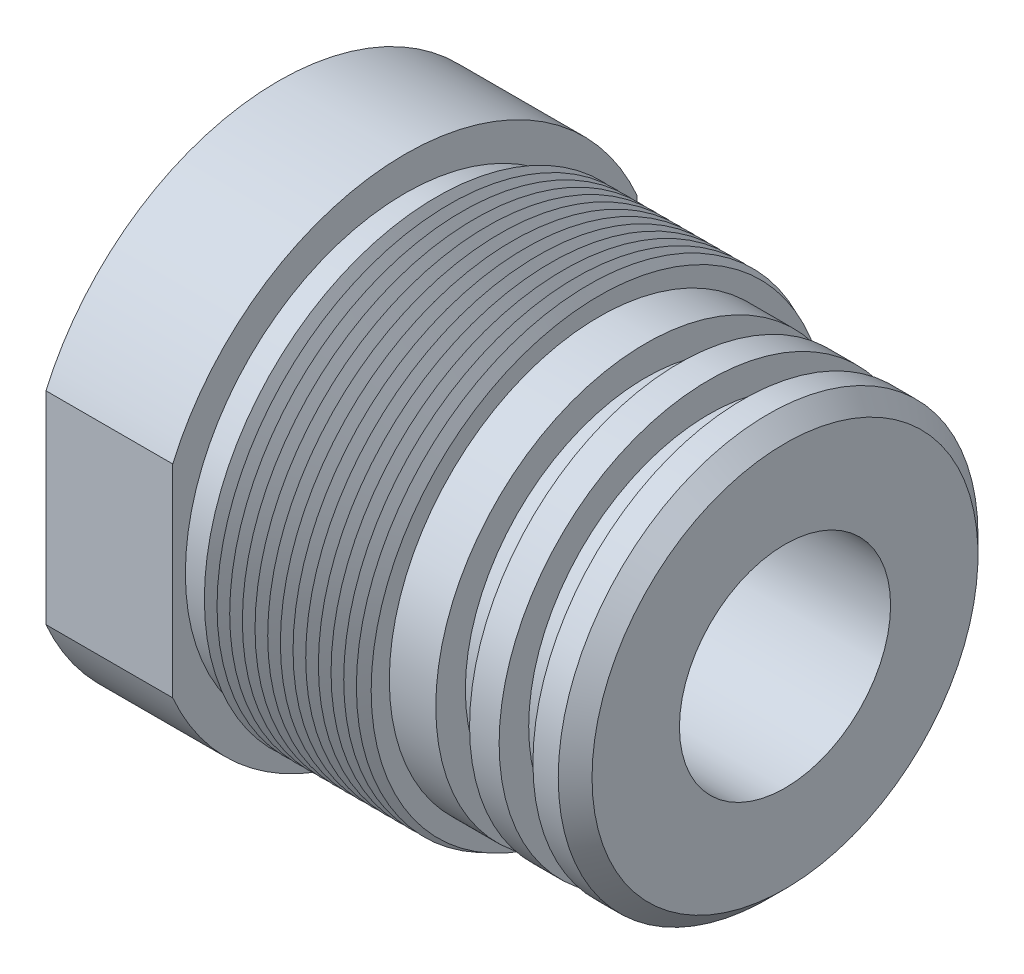
SolidWorks part; units mm, degrees
ref_plane "Front Plane" through (0, 0, 0) normal (0, 0, 1) x (1, 0, 0)
ref_plane "Top Plane" through (0, 0, 0) normal (0, 1, 0) x (1, 0, 0)
ref_plane "Right Plane" through (0, 0, 0) normal (1, 0, 0) x (0, 0, -1)
sketch "Sketch1" plane through (0, 0, 0) normal (0, 0, 1) x (1, 0, 0)
  line L0 (0, 0) -> (85.0332, 0) construction
  line L1 (0, 12.5) -> (60, 12.5)
  line L2 (0, 12.5) -> (0, 30)
  line L3 (0, 30) -> (15, 30)
  line L4 (15, 30) -> (15, 26)
  line L5 (15, 26) -> (18, 26)
  line L6 (18, 26) -> (18.75, 27.5)
  line L7 (18.75, 27.5) -> (19.5, 26)
  line L9 (19.5, 26) -> (20.25, 27.5)
  line L10 (20.25, 27.5) -> (21, 26)
  line L11 (21, 26) -> (21.75, 27.5)
  line L12 (21.75, 27.5) -> (22.5, 26)
  line L13 (22.5, 26) -> (23.25, 27.5)
  line L14 (23.25, 27.5) -> (24, 26)
  line L15 (24, 26) -> (24.75, 27.5)
  line L16 (24.75, 27.5) -> (25.5, 26)
  line L17 (25.5, 26) -> (26.25, 27.5)
  line L18 (26.25, 27.5) -> (27, 26)
  line L19 (27, 26) -> (27.75, 27.5)
  line L20 (27.75, 27.5) -> (28.5, 26)
  line L21 (28.5, 26) -> (29.25, 27.5)
  line L22 (29.25, 27.5) -> (30, 26)
  line L23 (30, 26) -> (30.75, 27.5)
  line L24 (30.75, 27.5) -> (31.5, 26)
  line L25 (31.5, 26) -> (32.25, 27.5)
  line L26 (32.25, 27.5) -> (33, 26)
  line L27 (33, 26) -> (33.75, 27.5)
  line L28 (33.75, 27.5) -> (34.5, 26)
  line L29 (34.5, 26) -> (35.25, 27.5)
  line L30 (35.25, 27.5) -> (36, 26)
  line L31 (36, 26) -> (36.75, 27.5)
  line L32 (36.75, 27.5) -> (37.5, 26)
  line L33 (37.5, 26) -> (38, 27)
  line L34 (58, 24.85) -> (60, 22.85)
  line L35 (60, 12.5) -> (60, 22.85)
  line L36 (58, 24.85) -> (55, 24.85)
  line L37 (38, 24.85) -> (38, 27)
  line L39 (38.25, 27.5) -> (39, 26) [skipped]
  line L40 (51, 24.85) -> (51, 21.35)
  line L41 (51, 21.35) -> (55, 21.35)
  line L42 (55, 24.85) -> (55, 21.35)
  line L44 (43.5, 24.85) -> (43.5, 21.35)
  line L45 (43.5, 21.35) -> (47.5, 21.35)
  line L46 (47.5, 24.85) -> (47.5, 21.35)
  line L47 (51, 24.85) -> (47.5, 24.85)
  line L48 (43.5, 24.85) -> (38, 24.85)
  dimension "D1" = 25
  dimension "D2" = 60
  dimension "D3" = 15
  dimension "D4" = 1.5
  dimension "D5" = 27.5
  dimension "D7" = 0.75
  dimension "D8" = 3
  dimension "D10" = 49.7
  dimension "D11" = 23
  dimension "D12" = 60
  dimension "D13" = 4
  dimension "D14" = 3.5
  dimension "D15" = 4
  dimension "D16" = 5
  dimension "D17" = 3.5
  dimension "D18" = 3.5
  dimension "D9" = 14
revolve "Revolve1" add sketch "Sketch1" angle 360 about L0
sketch "Sketch2" plane through (0, 0, 0) normal (-1, 0, 0) x (0, 0, 1)
  line L1 (-27.5, -38.3497) -> (27.5, -38.3497)
  line L2 (-27.5, -38.3497) -> (-27.5, 38.3497)
  line L3 (-27.5, 38.3497) -> (27.5, 38.3497)
  line L4 (27.5, -38.3497) -> (27.5, 38.3497)
  line L5 (-27.5, -38.3497) -> (27.5, 38.3497) construction
  line L6 (-27.5, 38.3497) -> (27.5, -38.3497) construction
  point P0 (0, 0)
  dimension "D1" = 55
extrude "Cut-Extrude1" cut sketch "Sketch2" against normal blind 17 flip side to cut
sketch "Sketch3" plane through (0, 0, 0) normal (0, 1, 0) x (1, 0, 0)
  line L0 (0, 12.5) -> (0.1287, 12.5) construction
  line L1 (60, 12.5) -> (0, 12.5) construction
  line L3 (0.1287, 15) -> (4.1287, 15) construction
  line L4 (4.1287, 15) -> (4.1287, 11.2199)
  line L5 (4.1287, 11.2199) -> (0.1287, 11.2199)
  line L6 (0.1287, 11.2199) -> (0.1287, 12.5)
  line L7 (0, 0) -> (26.0795, 0) construction
  line L8 (0.1287, 12.5) -> (61.3994, 12.5) construction
  line L9 (14.1287, 10.535) -> (22.1287, 10.535)
  line L10 (14.1287, 10.535) -> (14.1287, 18)
  line L11 (14.1287, 18) -> (22.1287, 18)
  line L12 (22.1287, 10.535) -> (22.1287, 18)
  line L13 (32.1287, 12.5) -> (32.1287, 11.2199)
  line L14 (32.1287, 12.5) -> (42.1287, 12.5) construction
  line L15 (32.1287, 12.5) -> (32.1287, 14.5)
  line L16 (32.1287, 14.5) -> (42.1287, 14.5)
  line L17 (42.1287, 12.5) -> (42.1287, 14.5)
  line L18 (32.1287, 11.2199) -> (42.1287, 11.2199)
  line L19 (42.1287, 11.2199) -> (42.1287, 12.5)
  line L20 (0.1287, 12.5) -> (0.5269, 15)
  line L21 (0.5269, 15) -> (4.1287, 15)
  point P21 (32.1287, 13.5)
  dimension "D1" = 15
  dimension "D2" = 4
  dimension "D3" = 36
  dimension "D4" = 8
  dimension "D5" = 10
  dimension "D6" = 2
  dimension "D7" = 10
  dimension "D8" = 10
revolve "Cut-Revolve1" cut sketch "Sketch3" angle 360 about L7
sketch "Sketch4" plane through (0, 0, 0) normal (-1, 0, 0) x (0, 0, 1)
  circle A0 centre (0, 0) radius 12.75
  dimension "D1" = 25.5
extrude "Cut-Extrude2" cut sketch "Sketch4" against normal blind 1
